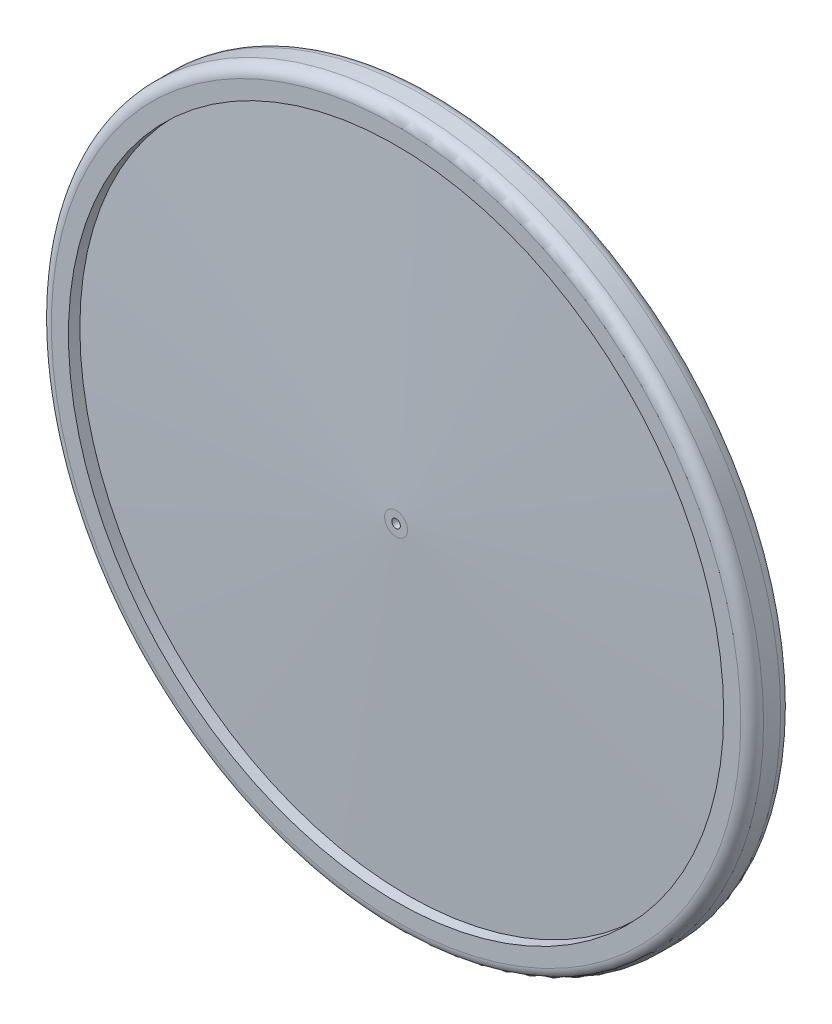
SolidWorks part; units mm, degrees
ref_plane "Front Plane" through (0, 0, 0) normal (0, 0, 1) x (1, 0, 0)
ref_plane "Top Plane" through (0, 0, 0) normal (0, 1, 0) x (1, 0, 0)
ref_plane "Right Plane" through (0, 0, 0) normal (1, 0, 0) x (0, 0, -1)
sketch "Sketch3" plane through (0, 0, 0) normal (0, 1, 0) x (1, 0, 0)
  line L0 (0, 0) -> (300, 0) construction
  line L6 (287.5, 17.5) -> (302.5, 17.5)
  line L7 (287.5, 17.5) -> (287.5, 7.5)
  line L8 (287.5, -17.5) -> (302.5, -17.5)
  line L9 (312.5, 7.5) -> (312.5, -7.5)
  line L10 (287.5, 17.5) -> (312.5, -17.5) construction
  line L11 (287.5, -17.5) -> (312.5, 17.5) construction
  line L12 (287.5, -7.5) -> (287.5, -17.5)
  line L13 (10.0282, -17.5) -> (287.5, -7.5)
  line L16 (0, 17.5) -> (10.0282, 17.5)
  line L18 (0, 0) -> (10.0282, 17.5) construction
  line L19 (0, 0) -> (10.0282, -17.5) construction
  line L20 (10.0282, 17.5) -> (287.5, 7.5)
  line L21 (10.0282, -17.5) -> (0, -17.5)
  line L22 (0, -17.5) -> (0, 17.5)
  arc A0 (302.5, -17.5) -> (312.5, -7.5) centre (302.5, -7.5) ccw
  arc A1 (302.5, 17.5) -> (312.5, 7.5) centre (302.5, 7.5) cw
  dimension "D4" = 10
  dimension "D1" = 300
  dimension "D2" = 35
  dimension "D3" = 25
  dimension "D5" = 10.0282
revolve "Revolve2" add sketch "Sketch3" angle 360 about L22
sketch "Sketch5" plane through (0, 0, 17.5) normal (0, 0, 1) x (1, 0, 0)
  circle A0 centre (0, 0) radius 3.75
  dimension "D1" = 7.5
extrude "Cut-Extrude1" cut sketch "Sketch5" against normal blind 72
